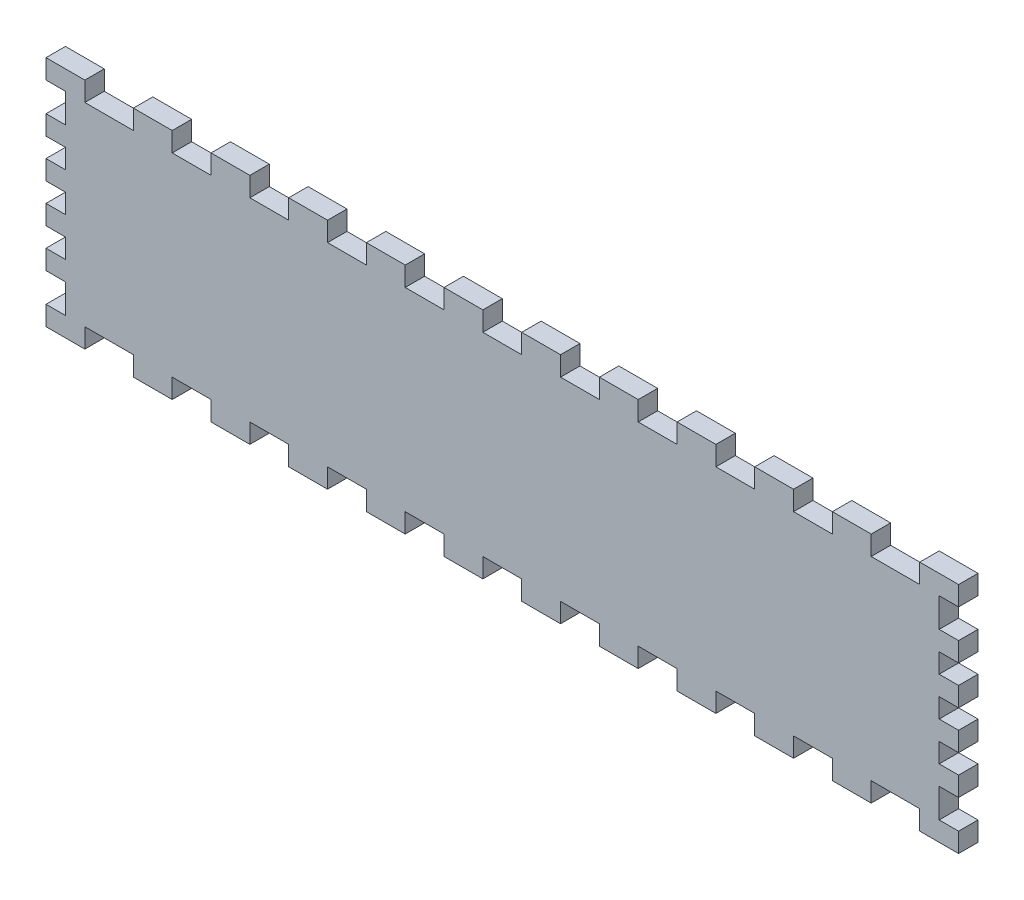
SolidWorks part; units mm, degrees
ref_plane "Front Plane" through (0, 0, 0) normal (0, 0, 1) x (1, 0, 0)
ref_plane "Top Plane" through (0, 0, 0) normal (0, 1, 0) x (1, 0, 0)
ref_plane "Right Plane" through (0, 0, 0) normal (1, 0, 0) x (0, 0, -1)
sketch "Sketch1" plane through (0, 0, 0) normal (0, 0, 1) x (1, 0, 0)
  line L1 (-149.225, -38.1) -> (149.225, -38.1)
  line L2 (-149.225, -38.1) -> (-149.225, 38.1)
  line L3 (-149.225, 38.1) -> (149.225, 38.1)
  line L4 (149.225, -38.1) -> (149.225, 38.1)
  line L5 (-149.225, -38.1) -> (149.225, 38.1) construction
  line L6 (-149.225, 38.1) -> (149.225, -38.1) construction
  point P0 (0, 0)
  dimension "D1" = 298.45
  dimension "D2" = 76.2
extrude "Boss-Extrude1" add sketch "Sketch1" along normal blind 6.35
sketch "Sketch2" plane through (0, 0, 0) normal (0, 0, 1) x (1, 0, 0)
  line L0 (149.225, -38.1) -> (149.225, 38.1) construction
  line L1 (107.95, -31.75) -> (95.25, -31.75)
  line L2 (107.95, -31.75) -> (107.95, -57.15)
  line L3 (107.95, -57.15) -> (95.25, -57.15)
  line L4 (95.25, -31.75) -> (95.25, -57.15)
  line L5 (107.95, -31.75) -> (95.25, -57.15) construction
  line L6 (107.95, -57.15) -> (95.25, -31.75) construction
  line L7 (-149.225, -38.1) -> (149.225, -38.1) construction
  point P0 (101.6, -44.45)
  dimension "D1" = 41.275
  dimension "D2" = 12.7
  dimension "D3" = 6.35
  dimension "D4" = 25.4
extrude "Cut-Extrude5" cut sketch "Sketch2" against normal through all and the other way through all contours L1 L4 L3 L2
pattern_linear "LPattern1" count 9 spacing 25.4 along (-1, 0, 0) of "Cut-Extrude5"
mirror "Mirror1" about plane through (0, 0, 0) normal (0, 1, 0) of "Cut-Extrude5", "LPattern1"
sketch "Sketch3" plane through (0, 0, 0) normal (0, 0, 1) x (1, 0, 0)
  line L0 (149.225, 38.1) -> (107.95, 38.1) construction
  line L1 (183.6235, 15.875) -> (142.875, 15.875)
  line L2 (183.6235, 15.875) -> (183.6235, 9.525)
  line L3 (183.6235, 9.525) -> (142.875, 9.525)
  line L4 (142.875, 15.875) -> (142.875, 9.525)
  line L5 (183.6235, 15.875) -> (142.875, 9.525) construction
  line L6 (183.6235, 9.525) -> (142.875, 15.875) construction
  line L7 (149.225, -38.1) -> (149.225, 38.1) construction
  line L8 (183.6235, 3.175) -> (142.875, 3.175)
  line L9 (183.6235, 3.175) -> (183.6235, -3.175)
  line L10 (183.6235, -3.175) -> (142.875, -3.175)
  line L11 (142.875, 3.175) -> (142.875, -3.175)
  line L12 (183.6235, 3.175) -> (142.875, -3.175) construction
  line L13 (183.6235, -3.175) -> (142.875, 3.175) construction
  line L14 (183.6235, -9.525) -> (142.875, -9.525)
  line L15 (183.6235, -9.525) -> (183.6235, -15.875)
  line L16 (183.6235, -15.875) -> (142.875, -15.875)
  line L17 (142.875, -9.525) -> (142.875, -15.875)
  line L18 (183.6235, -9.525) -> (142.875, -15.875) construction
  line L19 (183.6235, -15.875) -> (142.875, -9.525) construction
  line L24 (3.4925, 0) -> (-3.4925, 0) construction
  line L25 (168.275, 31.75) -> (142.875, 31.75)
  line L26 (168.275, 31.75) -> (168.275, 22.225)
  line L27 (168.275, 22.225) -> (142.875, 22.225)
  line L28 (183.6235, -22.225) -> (142.875, -22.225) [skipped]
  line L29 (183.6235, -22.225) -> (183.6235, -28.575) [skipped]
  line L30 (183.6235, -28.575) -> (142.875, -28.575) [skipped]
  line L31 (142.875, -22.225) -> (142.875, -28.575) [skipped]
  line L32 (183.6235, -22.225) -> (142.875, -28.575) construction
  line L33 (183.6235, -28.575) -> (142.875, -22.225) construction
  line L34 (142.875, 31.75) -> (142.875, 22.225)
  line L35 (168.275, 31.75) -> (142.875, 22.225) construction
  line L36 (168.275, 22.225) -> (142.875, 31.75) construction
  line L37 (168.275, -31.75) -> (168.275, -22.225)
  line L38 (168.275, -22.225) -> (142.875, -22.225)
  line L39 (142.875, -31.75) -> (142.875, -22.225)
  line L40 (168.275, -31.75) -> (142.875, -31.75)
  point P0 (163.2492, 12.7)
  point P9 (163.2492, -25.4)
  point P10 (155.575, 26.9875)
  point P11 (163.2492, 0)
  point P16 (163.2492, -12.7)
  dimension "D1" = 22.225
  dimension "D2" = 6.35
  dimension "D3" = 6.35
  dimension "D4" = 40.7485
  dimension "D6" = 6.35
  dimension "D7" = 6.35
  dimension "D8" = 9.525
  dimension "D9" = 25.4
  dimension "D10" = 6.35
  dimension "D5" = 4
extrude "Cut-Extrude7" cut sketch "Sketch3" along normal through all
mirror "Mirror2" about plane through (0, 0, 0) normal (1, 0, 0) of "Cut-Extrude7"
sketch "Sketch4" plane through (0, 0, 6.35) normal (0, 0, 1) x (1, 0, 0)
  line L1 (136.525, -31.75) -> (120.65, -31.75)
  line L2 (136.525, -31.75) -> (136.525, -57.15)
  line L3 (136.525, -57.15) -> (120.65, -57.15)
  line L4 (120.65, -31.75) -> (120.65, -57.15)
  line L6 (0, -3.4925) -> (0, 3.4925) construction
  line L7 (-120.65, -31.75) -> (-120.65, -57.15)
  line L8 (-136.525, -57.15) -> (-120.65, -57.15)
  line L9 (-136.525, -31.75) -> (-136.525, -57.15)
  line L10 (-136.525, -31.75) -> (-120.65, -31.75)
  line L11 (3.4925, 0) -> (-3.4925, 0) construction
  line L12 (-136.525, 31.75) -> (-120.65, 31.75)
  line L13 (-136.525, 31.75) -> (-136.525, 57.15)
  line L14 (-136.525, 57.15) -> (-120.65, 57.15)
  line L15 (-120.65, 31.75) -> (-120.65, 57.15)
  line L16 (120.65, 31.75) -> (120.65, 57.15)
  line L17 (136.525, 57.15) -> (120.65, 57.15)
  line L18 (136.525, 31.75) -> (136.525, 57.15)
  line L19 (136.525, 31.75) -> (120.65, 31.75)
  line L20 (107.95, -38.1) -> (149.225, -38.1) construction
  line L21 (149.225, -38.1) -> (149.225, -31.75) construction
  dimension "D1" = 6.35
  dimension "D2" = 12.7
  dimension "D3" = 25.4
  dimension "D4" = 15.875
extrude "Cut-Extrude8" cut sketch "Sketch4" against normal through all
